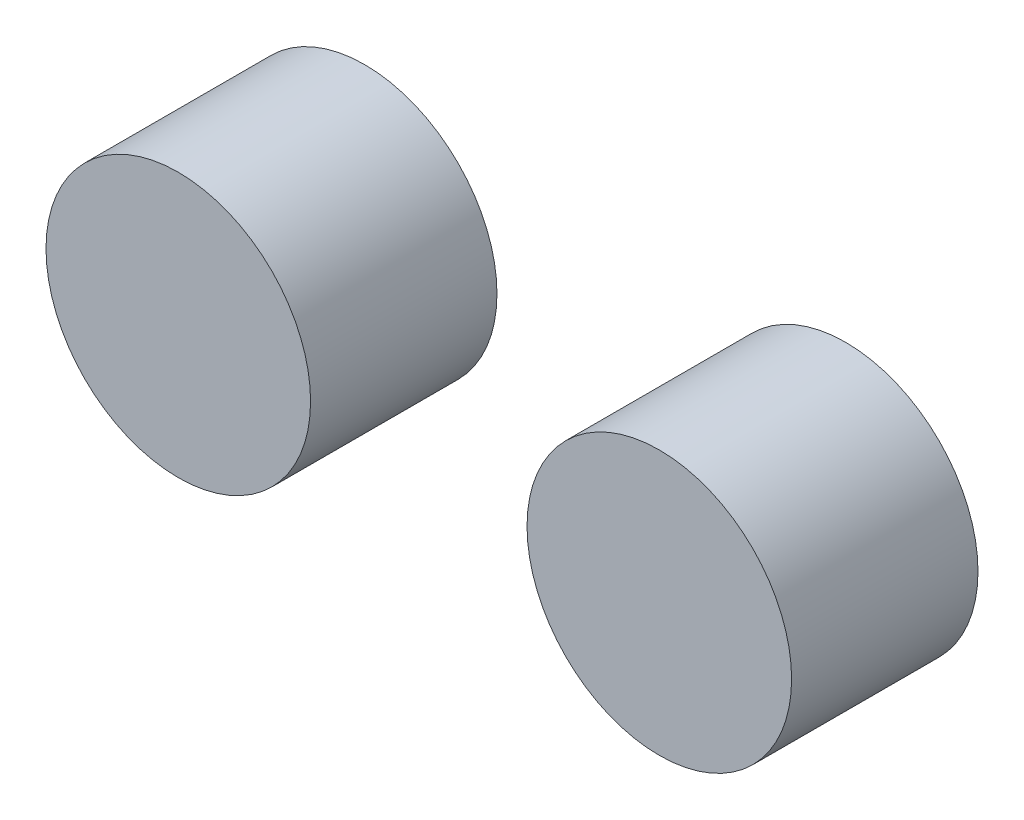
SolidWorks part; units mm, degrees
ref_plane "前视基准面" through (0, 0, 0) normal (0, 0, 1) x (1, 0, 0)
ref_plane "上视基准面" through (0, 0, 0) normal (0, 1, 0) x (1, 0, 0)
ref_plane "右视基准面" through (0, 0, 0) normal (1, 0, 0) x (0, 0, -1)
other "Configuration Table"
sketch "草图1" plane through (0, 0, 0) normal (0, 0, 1) x (1, 0, 0)
  circle A0 centre (-20, 60) radius 11
  circle A1 centre (20, 60) radius 11
extrude "R1_D22_visual_envelope_NOT_measured" add sketch "草图1" along normal blind 15.5 from offset 1.6 separate body
